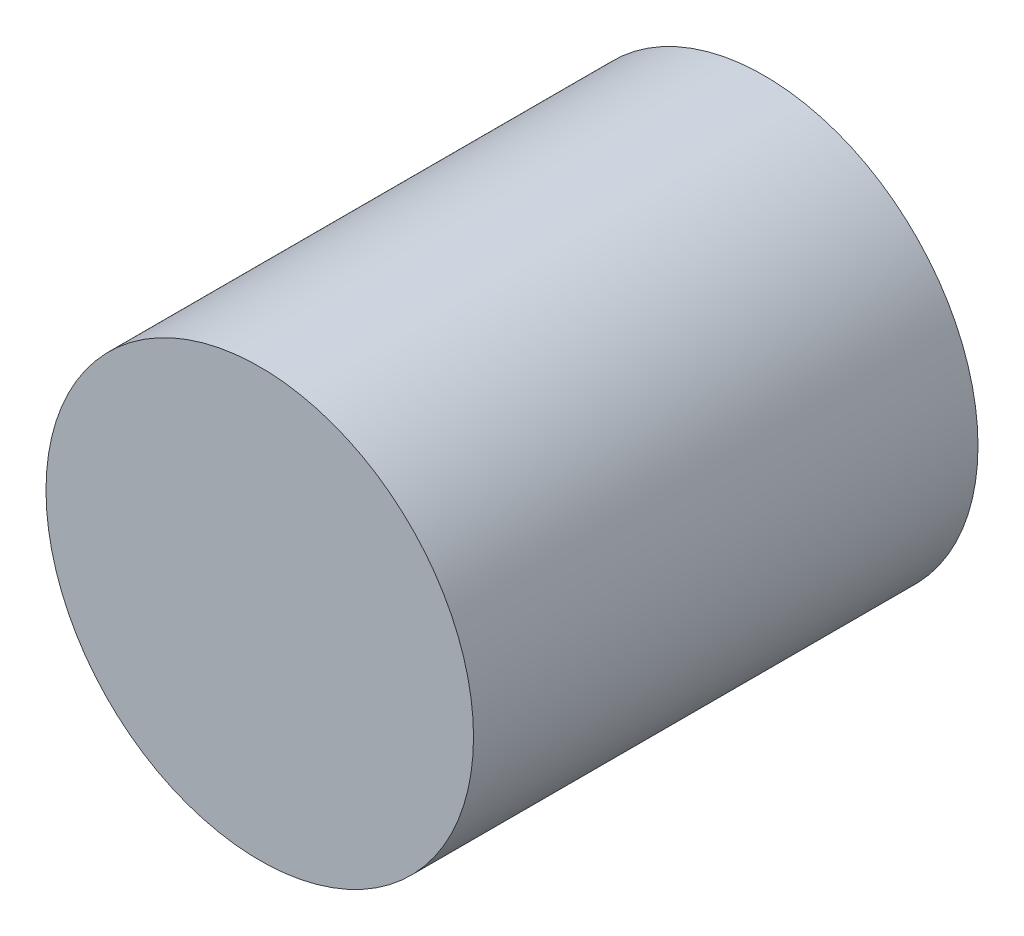
SolidWorks part; units mm, degrees
ref_plane "Front Plane" through (0, 0, 0) normal (0, 0, 1) x (1, 0, 0)
ref_plane "Top Plane" through (0, 0, 0) normal (0, 1, 0) x (1, 0, 0)
ref_plane "Right Plane" through (0, 0, 0) normal (1, 0, 0) x (0, 0, -1)
sketch "Sketch1" plane through (0, 0, 0) normal (0, 0, 1) x (1, 0, 0)
  circle A0 centre (0, 0) radius 25
  dimension "D1" = 50
extrude "Boss-Extrude1" add sketch "Sketch1" along normal blind 59
